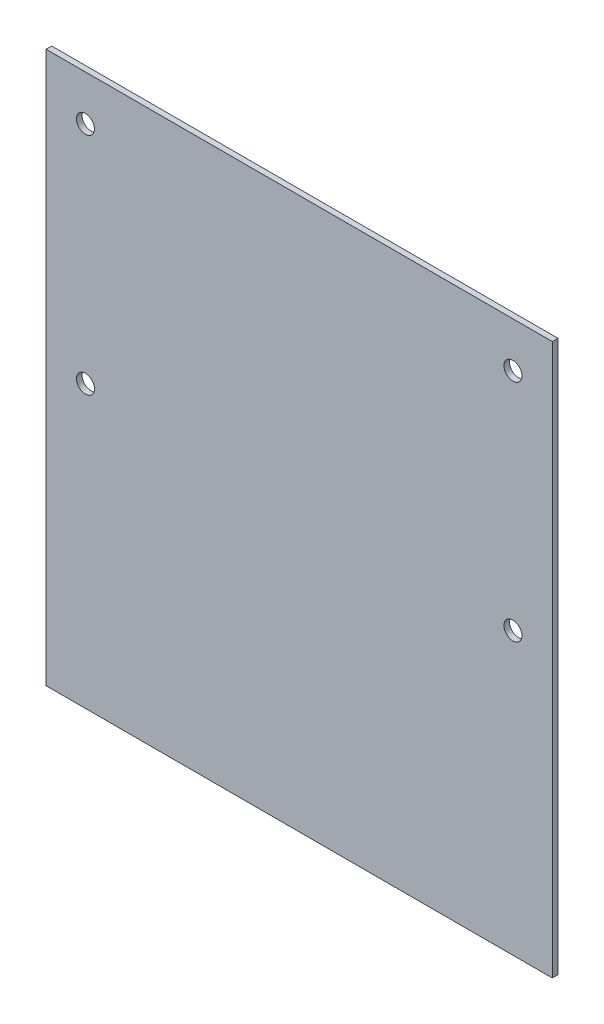
SolidWorks part; units mm, degrees
ref_plane "Plan de face" through (0, 0, 0) normal (0, 0, 1) x (1, 0, 0)
ref_plane "Plan de dessus" through (0, 0, 0) normal (0, 1, 0) x (1, 0, 0)
ref_plane "Plan de droite" through (0, 0, 0) normal (1, 0, 0) x (0, 0, -1)
sketch "Esquisse1" plane through (0, 0, 0) normal (0, 0, 1) x (1, 0, 0)
  line L1 (0, 0) -> (90, 0)
  line L2 (0, 0) -> (0, 98)
  line L3 (0, 98) -> (90, 98)
  line L4 (90, 0) -> (90, 98)
  dimension "D1" = 90
  dimension "D2" = 98
extrude "Boss.-Extru.1" add sketch "Esquisse1" along normal blind 1
sketch "Esquisse2" plane through (0, 0, 1) normal (0, 0, 1) x (1, 0, 0)
  line L0 (45, 0) -> (45, 98) construction
  line L1 (0, 0) -> (90, 0) construction
  line L2 (90, 98) -> (0, 98) construction
  line L3 (7, 50) -> (7, 90) construction
  line L4 (83, 50) -> (83, 90) construction
  circle A0 centre (7, 50) radius 1.6
  circle A1 centre (7, 90) radius 1.6
  circle A2 centre (83, 90) radius 1.6
  circle A3 centre (83, 50) radius 1.6
  dimension "D1" = 76
  dimension "D2" = 50
  dimension "D3" = 3.2
  dimension "D4" = 40
extrude "Enlèv. mat.-Extru.1" cut sketch "Esquisse2" against normal through all both and the other way through all
